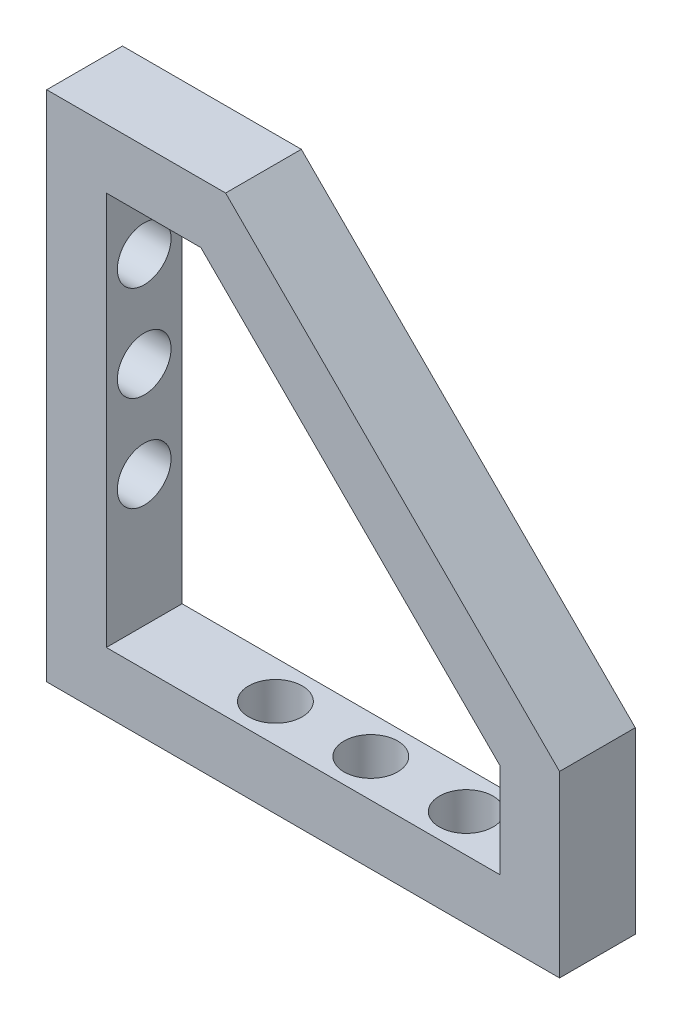
SolidWorks part; units mm, degrees
ref_plane "Front Plane" through (0, 0, 0) normal (0, 0, 1) x (1, 0, 0)
ref_plane "Top Plane" through (0, 0, 0) normal (0, 1, 0) x (1, 0, 0)
ref_plane "Right Plane" through (0, 0, 0) normal (1, 0, 0) x (0, 0, -1)
sketch "Sketch1" plane through (0, 0, 0) normal (0, 0, 1) x (1, 0, 0)
  line L0 (0, 0) -> (0, 43)
  line L1 (0, 43) -> (15, 43)
  line L2 (15, 43) -> (43, 15)
  line L3 (43, 15) -> (43, 0)
  line L4 (43, 0) -> (0, 0)
  line L5 (38, 5) -> (5, 5)
  line L6 (5, 5) -> (5, 38)
  line L7 (5, 38) -> (12.9289, 38)
  line L8 (12.9289, 38) -> (38, 12.9289)
  line L9 (38, 12.9289) -> (38, 5)
  dimension "D1" = 15
  dimension "D2" = 43
  dimension "D3" = 5
extrude "Boss-Extrude1" add sketch "Sketch1" along normal blind 6.35
sketch "Sketch2" plane through (0, 0, 0) normal (0, -1, 0) x (1, 0, 0)
  line L1 (-7.1359, 3.175) -> (-4.4202, 3.175) construction
  line L2 (0, 6.35) -> (0, 0) construction
  circle A0 centre (16, 3.175) radius 2.25
  circle A1 centre (24, 3.175) radius 2.25
  circle A2 centre (32, 3.175) radius 2.25
  point P6 (0, 3.175)
  point P9 (0, 0)
  dimension "D1" = 4.5
  dimension "D2" = 16
  dimension "D4" = 8
  dimension "D3" = 3
extrude "Cut-Extrude1" cut sketch "Sketch2" against normal up to surface (5 mm away) up to face at (21.5, 5, 3.175)
sketch "Sketch3" plane through (0, 0, 0) normal (-1, 0, 0) x (0, 0, 1)
  line L0 (3.175, 1.4904) -> (3.175, 6.9756) construction
  line L1 (6.35, 0) -> (0, 0) construction
  circle A0 centre (3.175, 16) radius 2.25
  circle A1 centre (3.175, 24) radius 2.25
  circle A2 centre (3.175, 32) radius 2.25
  point P6 (3.175, 0)
  dimension "D1" = 4.5
  dimension "D2" = 16
  dimension "D4" = 8
  dimension "D3" = 3
extrude "Cut-Extrude2" cut sketch "Sketch3" against normal up to surface (5 mm away) up to face at (5, 21.5, 3.175)
